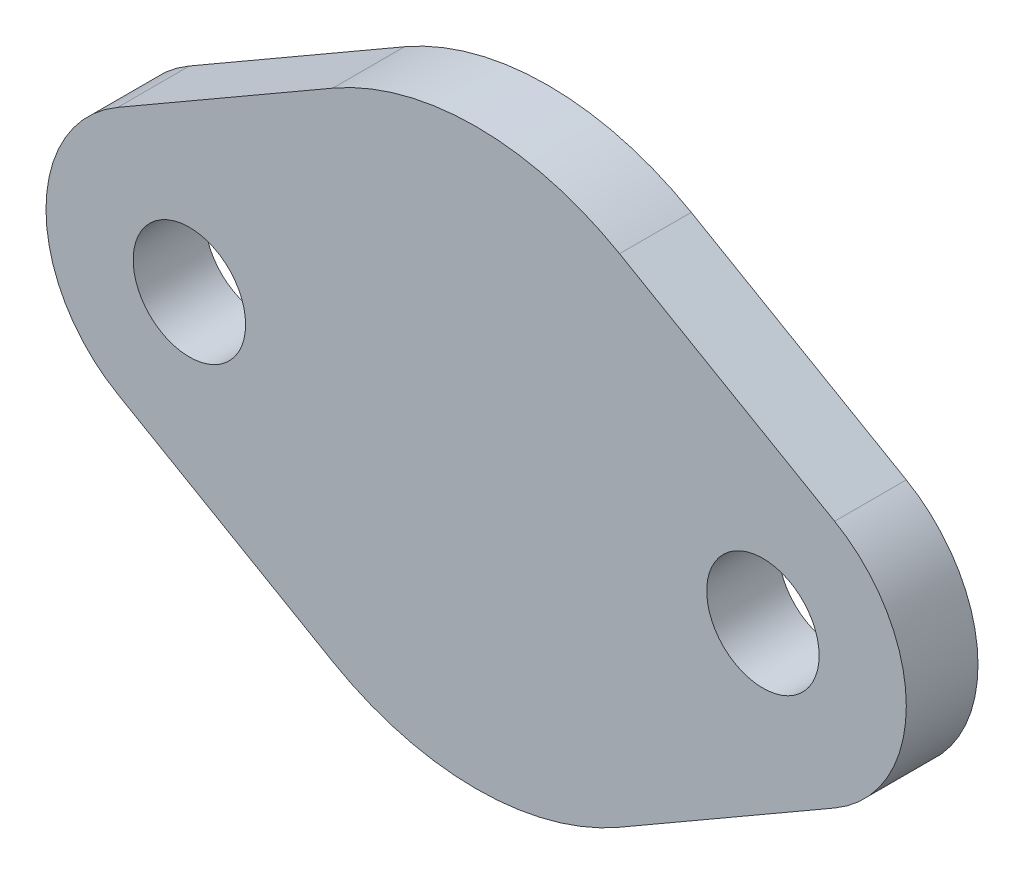
SolidWorks part; units mm, degrees
material "PET"
ref_plane "Front Plane" through (0, 0, 0) normal (0, 0, 1) x (1, 0, 0)
ref_plane "Top Plane" through (0, 0, 0) normal (0, 1, 0) x (1, 0, 0)
ref_plane "Right Plane" through (0, 0, 0) normal (1, 0, 0) x (0, 0, -1)
sketch "Sketch1" plane through (0, 0, 0) normal (0, 0, 1) x (1, 0, 0)
  line L0 (-12.7, 0) -> (12.7, 0) construction
  line L1 (-15.875, 5.4993) -> (-6.35, 10.9985)
  line L2 (6.35, 10.9985) -> (15.875, 5.4993)
  line L3 (-15.875, -5.4993) -> (-6.35, -10.9985)
  line L4 (15.875, -5.4993) -> (6.35, -10.9985)
  circle A0 centre (-12.7, 0) radius 2.4892
  circle A1 centre (12.7, 0) radius 2.4892
  arc A2 (-6.35, -10.9985) -> (6.35, -10.9985) centre (0, 0) ccw
  arc A3 (-15.875, 5.4993) -> (-15.875, -5.4993) centre (-12.7, 0) ccw
  arc A4 (15.875, -5.4993) -> (15.875, 5.4993) centre (12.7, 0) ccw
  arc A5 (6.35, 10.9985) -> (-6.35, 10.9985) centre (0, 0) ccw
  point P4 (0, 0)
  dimension "D1" = 4.9784
  dimension "D2" = 25.4
  dimension "D3" = 25.4
  dimension "D4" = 12.7
extrude "Boss-Extrude1" add sketch "Sketch1" along normal mid plane 3.175
